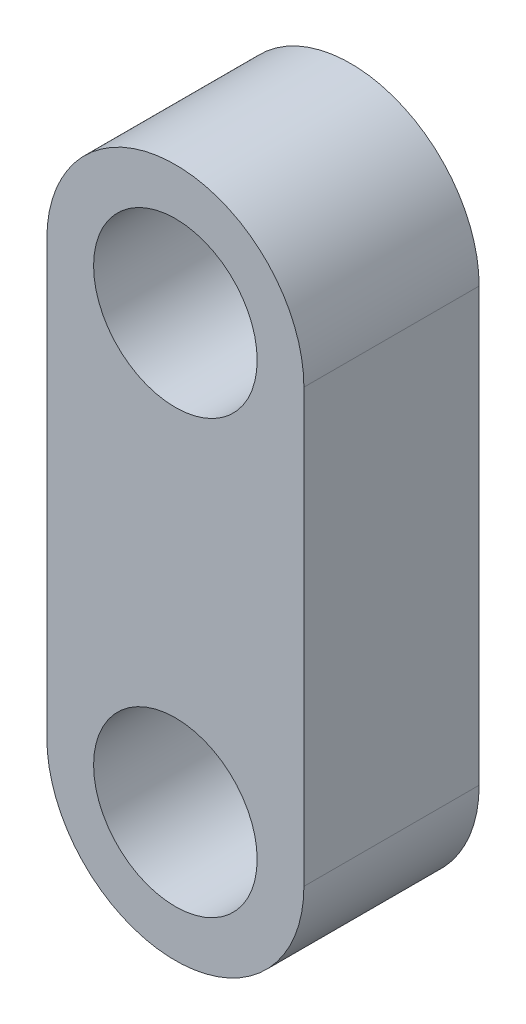
SolidWorks part; units mm, degrees
ref_plane "前视基准面" through (0, 0, 0) normal (0, 0, 1) x (1, 0, 0)
ref_plane "上视基准面" through (0, 0, 0) normal (0, 1, 0) x (1, 0, 0)
ref_plane "右视基准面" through (0, 0, 0) normal (1, 0, 0) x (0, 0, -1)
sketch "草图1" plane through (0, 0, 0) normal (0, 0, 1) x (1, 0, 0)
  line L2 (0, 0) -> (0, -37)
  line L4 (22, 0) -> (22, -37)
  arc A0 (22, 0) -> (0, 0) centre (11, 0) ccw
  arc A1 (0, -37) -> (22, -37) centre (11, -37) ccw
  circle A2 centre (11, 0) radius 7
  circle A3 centre (11, -37) radius 7
  dimension "D3" = 14
  dimension "D4" = 14
  dimension "D1" = 22
  dimension "D2" = 37
extrude "拉伸1" add sketch "草图1" along normal blind 15
ref_plane "基准面1" through (0, 0, 15) normal (0, -1, 0) x (1, 0, 0)
